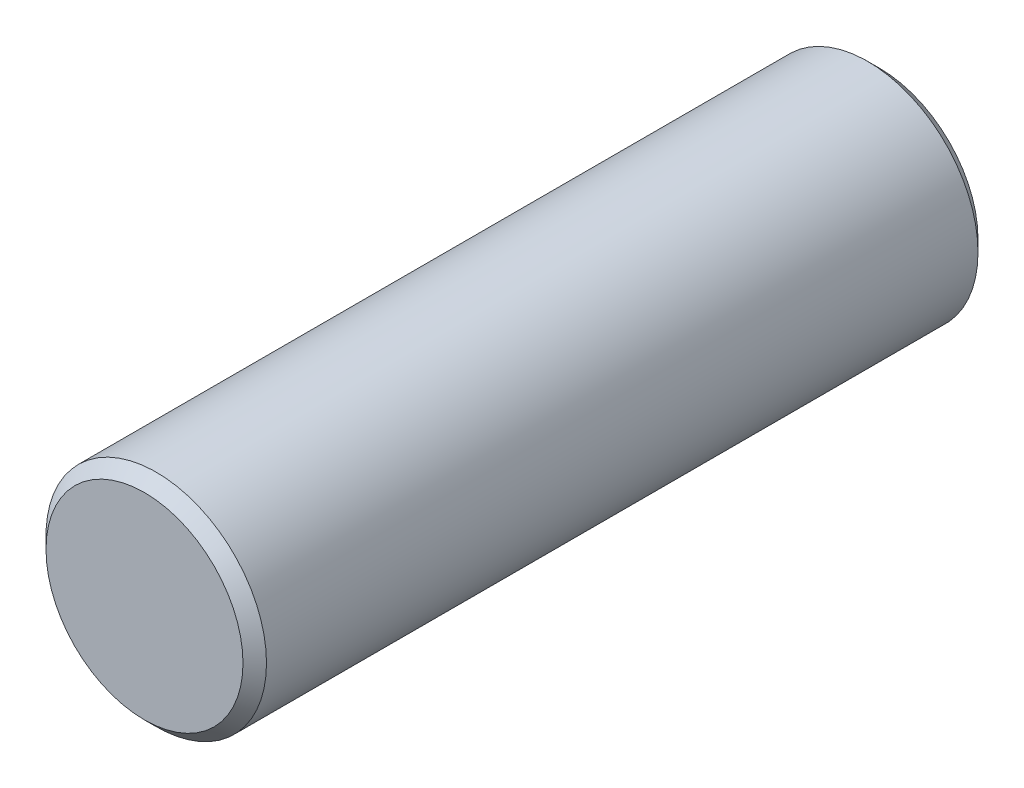
SolidWorks part; units mm, degrees
ref_plane "Front Plane" through (0, 0, 0) normal (0, 0, 1) x (1, 0, 0)
ref_plane "Top Plane" through (0, 0, 0) normal (0, 1, 0) x (1, 0, 0)
ref_plane "Right Plane" through (0, 0, 0) normal (1, 0, 0) x (0, 0, -1)
sketch "Sketch1" plane through (0, 0, 0) normal (0, 0, 1) x (1, 0, 0)
  circle A0 centre (0, 0) radius 2.3813
extrude "Boss-Extrude1" add sketch "Sketch1" along normal blind 15.875
chamfer "Chamfer2" distance 0.254 angle 45 2 edges at (2.3813, 0, 0) (2.3813, 0, 15.875)
